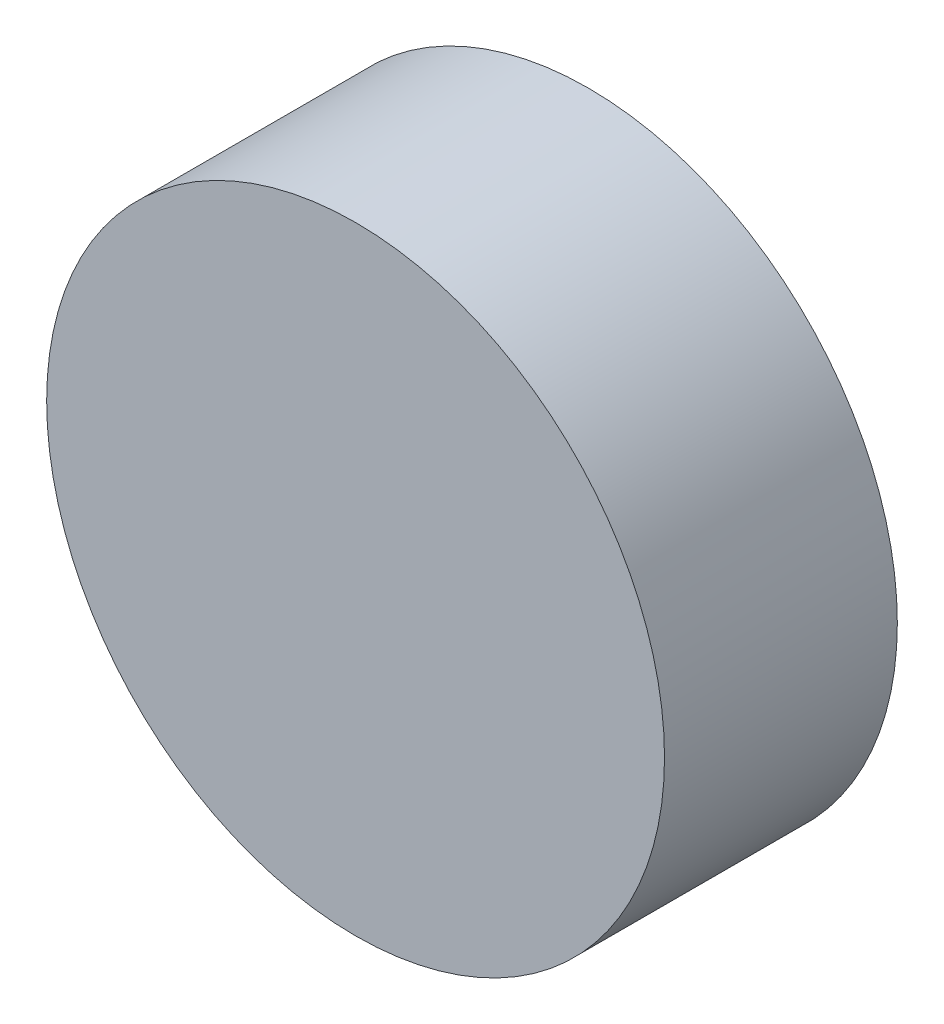
SolidWorks part; units mm, degrees
ref_plane "Front Plane" through (0, 0, 0) normal (0, 0, 1) x (1, 0, 0)
ref_plane "Top Plane" through (0, 0, 0) normal (0, 1, 0) x (1, 0, 0)
ref_plane "Right Plane" through (0, 0, 0) normal (1, 0, 0) x (0, 0, -1)
sketch "Sketch1" plane through (0, 0, 0) normal (0, 0, 1) x (1, 0, 0)
  circle A0 centre (0, 0) radius 34.5
extrude "Boss-Extrude1" add sketch "Sketch1" along normal blind 26
